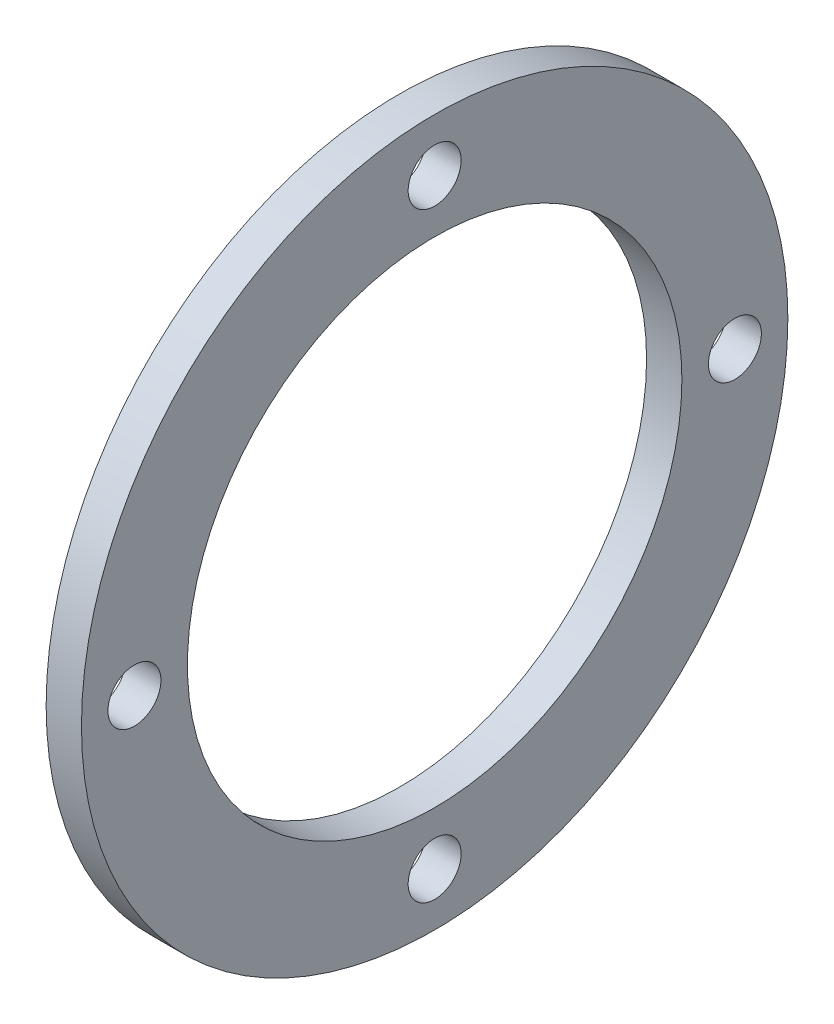
SolidWorks part; units mm, degrees
material "2024-T4"
ref_plane "Front Plane" through (0, 0, 0) normal (0, 0, 1) x (1, 0, 0)
ref_plane "Top Plane" through (0, 0, 0) normal (0, 1, 0) x (1, 0, 0)
ref_plane "Right Plane" through (0, 0, 0) normal (1, 0, 0) x (0, 0, -1)
sketch "Sketch1" plane through (0, 0, 0) normal (1, 0, 0) x (0, 0, -1)
  line L0 (0, 0) -> (0, 17) construction
  circle A0 centre (0, 0) radius 14
  circle A1 centre (0, 0) radius 20
  circle A2 centre (0, 17) radius 1.5
  circle A3 centre (17, 0) radius 1.5
  circle A4 centre (0, -17) radius 1.5
  circle A5 centre (-17, 0) radius 1.5
  point P14 (0, 0)
  dimension "D1" = 28
  dimension "D2" = 40
  dimension "D3" = 3
  dimension "D4" = 17
  dimension "D5" = 4
extrude "Boss-Extrude1" add sketch "Sketch1" along normal blind 2
sketch "Sketch2" [suppressed] plane through (0, 0, 0) normal (0, 0, 1) x (1, 0, 0)
  line L0 (0, 8.5) -> (2, 8.5)
  line L1 (2, 8.5) -> (2, 4)
  line L2 (2, 4) -> (4, 4)
  line L3 (4, 4) -> (4, 11)
  line L4 (4, 11) -> (0, 11)
  line L5 (0, 11) -> (0, 8.5)
  line L6 (0, 0) -> (3.7209, 0) construction
  dimension "D1" = 2
  dimension "D2" = 2
  dimension "D3" = 17
  dimension "D4" = 22
  dimension "D5" = 8
revolve "Revolve1" [suppressed] add sketch "Sketch2" angle 360 about L6
sketch "Sketch3" [suppressed] plane through (4, 0, 0) normal (1, 0, 0) x (0, 0, -1)
  line L0 (0, 0) -> (0, 6) construction
  circle A0 centre (0, 6) radius 1
  circle A1 centre (6, 0) radius 1
  circle A2 centre (0, -6) radius 1
  circle A3 centre (-6, 0) radius 1
  point P12 (0, 0)
  dimension "D2" = 2
  dimension "D1" = 6
  dimension "D3" = 4
extrude "Cut-Extrude2" [suppressed] cut sketch "Sketch3" against normal blind 7
